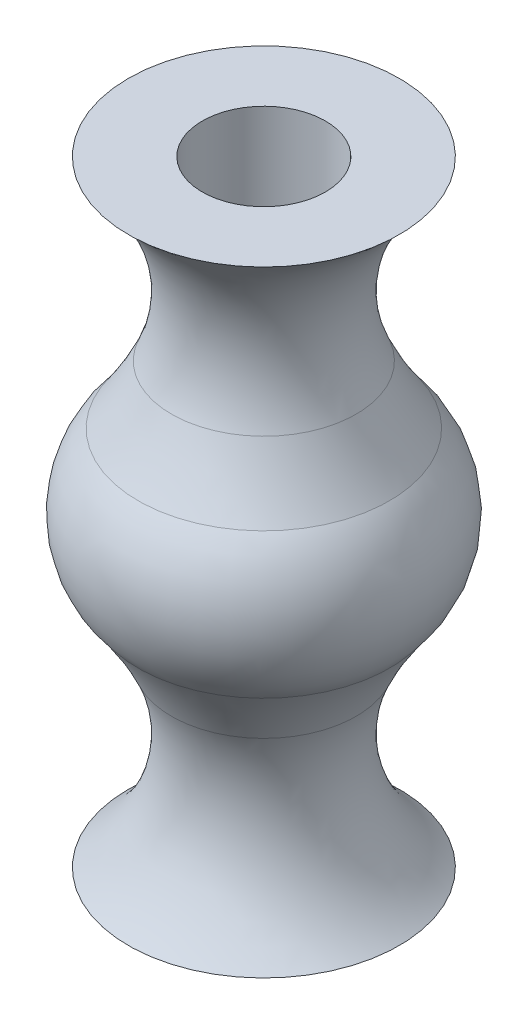
SolidWorks part; units mm, degrees
ref_plane "Plan de face" through (0, 0, 0) normal (0, 0, 1) x (1, 0, 0)
ref_plane "Plan de dessus" through (0, 0, 0) normal (0, 1, 0) x (1, 0, 0)
ref_plane "Plan de droite" through (0, 0, 0) normal (1, 0, 0) x (0, 0, -1)
sketch "Esquisse1" plane through (0, 0, 0) normal (0, 0, 1) x (1, 0, 0)
  line L0 (0, 5) -> (0, -5)
  line L1 (0, -2) -> (0, -84.9565) construction
  line L2 (0, -2.1251) -> (-1.5, -2.1251) construction
  line L3 (0, 0) -> (-3.8878, 0) construction
  line L4 (-2.2, -5) -> (0, -5)
  line L5 (-2.2, 5) -> (0, 5)
  arc A1 (-1.5, 2.1251) -> (-2.2, 5) centre (-3.7015, 3.1117) ccw
  arc A2 (-2.0423, 1.1775) -> (-1.5, 2.1251) centre (-6.5696, 4.3971) ccw
  arc A3 (-2.0423, -1.1775) -> (-1.5, -2.1251) centre (-6.5696, -4.3971) cw
  arc A4 (-1.5, -2.1251) -> (-2.2, -5) centre (-3.7015, -3.1117) cw
  arc A5 (-2.0423, 1.1775) -> (-2.0423, -1.1775) centre (-0.7567, 0) ccw
  dimension "D2" = 1.5
  dimension "D3" = 1.5
  dimension "D4" = 2.2
  dimension "D5" = 10
revolve "Révolution2" add sketch "Esquisse1" angle 360 about L1
sketch "Esquisse4" plane through (0, 5, 0) normal (0, 1, 0) x (1, 0, 0)
  circle A0 centre (0, 0) radius 1
  dimension "D1" = 2
sketch "Esquisse5" plane through (0, -5, 0) normal (0, -1, 0) x (-1, 0, 0)
  circle A0 centre (0, 0) radius 1
  dimension "D1" = 2
extrude "Enlèv. mat.-Extru.2" cut sketch "Esquisse5" against normal blind 10
sketch "Esquisse6" plane through (0, 0, 0) normal (0, 1, 0) x (1, 0, 0)
  circle A0 centre (0, 0) radius 2.5
